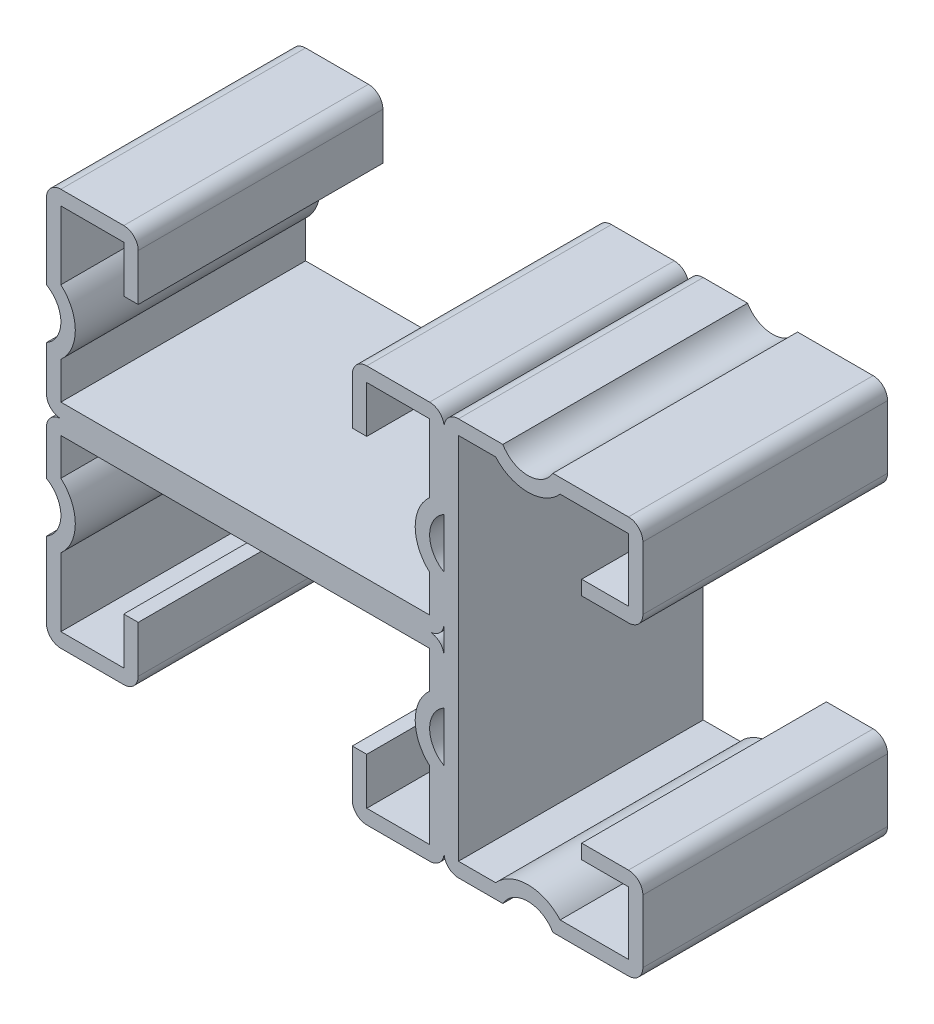
SolidWorks part; units mm, degrees
ref_plane "Plane1" through (0, 0, 0) normal (0, 0, 1) x (1, 0, 0)
ref_plane "Plane2" through (0, 0, 0) normal (0, 1, 0) x (1, 0, 0)
ref_plane "Plane3" through (0, 0, 0) normal (1, 0, 0) x (0, 0, -1)
sketch "Sketch1" plane through (0, 0, 0) normal (0, 0, 1) x (1, 0, 0)
  line L0 (-20.6375, 19.1389) -> (-20.6375, 11.2952)
  line L1 (-20.6375, 6.1038) -> (-20.6375, 1.4986)
  line L2 (-19.1389, 0) -> (19.1389, 0)
  line L3 (20.6375, 1.4986) -> (20.6375, 6.1038)
  line L4 (20.6375, 11.2952) -> (20.6375, 19.1389)
  line L5 (19.1389, 20.6375) -> (12.6111, 20.6375)
  line L6 (11.1125, 19.1389) -> (11.1125, 14.2875)
  line L7 (-19.1389, 20.6375) -> (-12.6111, 20.6375)
  line L8 (-11.1125, 19.1389) -> (-11.1125, 14.2875)
  line L9 (19.1389, 3.4236) -> (19.1389, 6.4516) construction
  line L10 (-19.1389, 15.1511) -> (-19.1389, 3.4236) construction
  line L11 (-12.6111, 19.1389) -> (-12.6111, 14.2875)
  line L12 (-19.1389, 19.1389) -> (-12.6111, 19.1389)
  line L13 (-19.1389, 19.1389) -> (-19.1389, 12.0505)
  line L14 (-19.1389, 5.3485) -> (-19.1389, 1.4986)
  line L15 (-19.1389, 1.4986) -> (19.1389, 1.4986)
  line L16 (19.1389, 1.4986) -> (19.1389, 5.3485)
  line L17 (19.1389, 12.0505) -> (19.1389, 19.1389)
  line L18 (19.1389, 19.1389) -> (12.6111, 19.1389)
  line L19 (12.6111, 19.1389) -> (12.6111, 14.2875)
  line L20 (-12.6111, 14.2875) -> (-11.1125, 14.2875)
  line L21 (11.1125, 14.2875) -> (12.6111, 14.2875)
  arc A0 (20.6375, 11.2952) -> (20.6375, 6.1038) centre (22.1361, 8.6995) ccw
  arc A1 (-20.6375, 6.1038) -> (-20.6375, 11.2952) centre (-22.1361, 8.6995) ccw
  arc A2 (-12.6111, 20.6375) -> (-11.1125, 19.1389) centre (-12.6111, 19.1389) cw
  arc A3 (-20.6375, 19.1389) -> (-19.1389, 20.6375) centre (-19.1389, 19.1389) cw
  arc A4 (-19.1389, 0) -> (-20.6375, 1.4986) centre (-19.1389, 1.4986) cw
  arc A5 (20.6375, 1.4986) -> (19.1389, 0) centre (19.1389, 1.4986) cw
  arc A6 (19.1389, 20.6375) -> (20.6375, 19.1389) centre (19.1389, 19.1389) cw
  arc A7 (11.1125, 19.1389) -> (12.6111, 20.6375) centre (12.6111, 19.1389) cw
  arc A8 (-19.1389, 5.3485) -> (-19.1389, 12.0505) centre (-22.1361, 8.6995) ccw
  arc A9 (19.1389, 12.0505) -> (19.1389, 5.3485) centre (22.1361, 8.6995) ccw
  dimension "D9" = 2.9972
  dimension "D10" = 2.9972
  dimension "Width" = 41.275
  dimension "D6" = 22.225
  dimension "edge" = 9.525
  dimension "Lip" = 6.35
  dimension "D1" = 20.6375
  dimension "D2" = 8.6995
  dimension "gauge" = 1.4986
extrude "Base-Extrude" add sketch "Sketch1" along normal mid plane 25.4
mirror "Mirror1" about plane through (0, 0, 0) normal (0, 1, 0) of "Base-Extrude"
sketch "Sketch2" plane through (20.1612, 0.1588, 0) normal (0, 0, 1) x (0, -1, 0)
  line L0 (-20.4788, 19.6152) -> (-20.4788, 11.7714)
  line L1 (-20.4788, 6.5801) -> (-20.4788, 1.9749)
  line L2 (-18.9802, 0.4763) -> (19.2976, 0.4763)
  line L3 (20.7962, 1.9749) -> (20.7962, 6.5801)
  line L4 (20.7962, 11.7714) -> (20.7962, 19.6152)
  line L5 (19.2977, 21.1138) -> (12.7698, 21.1138)
  line L6 (11.2712, 19.6152) -> (11.2712, 14.7638)
  line L7 (-18.9802, 21.1138) -> (-12.4523, 21.1138)
  line L8 (-10.9538, 19.6152) -> (-10.9538, 14.7638)
  line L9 (19.2976, 3.8998) -> (19.2976, 6.9279) construction
  line L10 (-18.9802, 15.6274) -> (-18.9802, 3.8998) construction
  line L11 (-12.4523, 19.6152) -> (-12.4524, 14.7638)
  line L12 (-18.9802, 19.6152) -> (-12.4523, 19.6152)
  line L13 (-18.9802, 19.6152) -> (-18.9802, 12.5267)
  line L14 (-18.9802, 5.8248) -> (-18.9802, 1.9749)
  line L15 (-18.9802, 1.9749) -> (19.2976, 1.9749)
  line L16 (19.2976, 1.9749) -> (19.2976, 5.8248)
  line L17 (19.2977, 12.5267) -> (19.2977, 19.6152)
  line L18 (19.2977, 19.6152) -> (12.7698, 19.6152)
  line L19 (12.7698, 19.6152) -> (12.7698, 14.7638)
  line L20 (-12.4524, 14.7638) -> (-10.9538, 14.7638)
  line L21 (11.2712, 14.7638) -> (12.7698, 14.7638)
  arc A0 (20.7962, 11.7714) -> (20.7962, 6.5801) centre (22.2948, 9.1758) ccw
  arc A1 (-20.4788, 6.5801) -> (-20.4788, 11.7714) centre (-21.9774, 9.1758) ccw
  arc A2 (-12.4523, 21.1138) -> (-10.9538, 19.6152) centre (-12.4523, 19.6152) cw
  arc A3 (-20.4788, 19.6152) -> (-18.9802, 21.1138) centre (-18.9802, 19.6152) cw
  arc A4 (-18.9802, 0.4763) -> (-20.4788, 1.9749) centre (-18.9802, 1.9749) cw
  arc A5 (20.7962, 1.9749) -> (19.2976, 0.4763) centre (19.2976, 1.9749) cw
  arc A6 (19.2977, 21.1138) -> (20.7962, 19.6152) centre (19.2977, 19.6152) cw
  arc A7 (11.2712, 19.6152) -> (12.7698, 21.1138) centre (12.7698, 19.6152) cw
  arc A8 (-18.9802, 5.8248) -> (-18.9802, 12.5267) centre (-21.9774, 9.1758) ccw
  arc A9 (19.2977, 12.5267) -> (19.2976, 5.8248) centre (22.2948, 9.1758) ccw
  dimension "D1" = 20.6375
  dimension "D9" = 2.9972
  dimension "D10" = 2.9972
  dimension "D2" = 8.6995
  dimension "D3" = 20.6375
  dimension "Width" = 41.275
  dimension "D6" = 22.225
  dimension "edge" = 9.525
  dimension "Lip" = 6.35
  dimension "D4" = 20.6375
  dimension "gauge" = 1.4986
extrude "Boss-Extrude1" add sketch "Sketch2" along normal mid plane 25.4
equation "\"D1@Sketch1\" = \"Width@Sketch1\" / 2"
equation "\"D6@Sketch1\" = \"Width@Sketch1\" - 2 * \"edge@Sketch1\""
equation "\"D10@Sketch1\" = 2 * \"gauge@Sketch1\""
equation "\"D9@Sketch1\" = \"D10@Sketch1\""
equation "\"D1@Boss-Extrude1\" = \"D1@Base-Extrude\""
